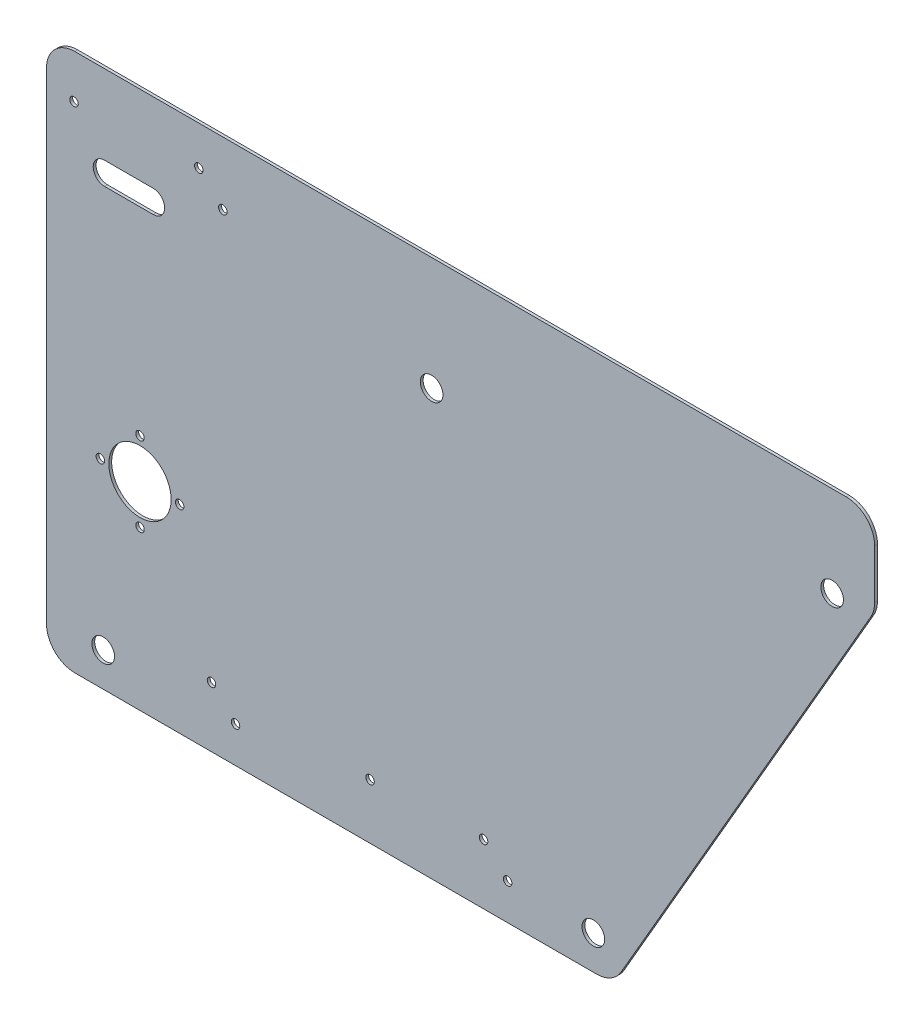
SolidWorks part; units mm, degrees
ref_plane "Front Plane" through (0, 0, 0) normal (0, 0, 1) x (1, 0, 0)
ref_plane "Top Plane" through (0, 0, 0) normal (0, 1, 0) x (1, 0, 0)
ref_plane "Right Plane" through (0, 0, 0) normal (1, 0, 0) x (0, 0, -1)
sketch "Sketch1" plane through (0, 0, 0) normal (0, 0, 1) x (1, 0, 0)
  line L0 (100, 80) -> (192.376, 80)
  line L1 (-100, -80) -> (100, -80)
  line L2 (-100, -80) -> (-100, 80)
  line L3 (-100, 80) -> (100, 80)
  line L4 (100, -80) -> (100, 80)
  line L5 (-100, -80) -> (100, 80) construction
  line L6 (-100, 80) -> (100, -80) construction
  line L7 (192.376, 80) -> (100, -80)
  line L8 (100, 80) -> (100, -80)
  line L10 (-100, 80) -> (192.376, 80)
  line L11 (-100, 80) -> (-100, 110)
  line L12 (-100, 110) -> (192.376, 110)
  line L13 (192.376, 80) -> (192.376, 110)
  point P0 (0, 0)
  dimension "D1" = 160
  dimension "D2" = 200
  dimension "D3" = 30
  dimension "D4" = 30
extrude "Boss-Extrude1" add sketch "Sketch1" along normal blind 1 contours L1 L4 L3 L2 | L7 L0 L4 | L11 L10 L13 L12
fillet "Fillet1" radius 10 5 edges at (100, -80, 0.5) (-100, -80, 0.5) (192.376, 110, 0.5) (-100, 110, 0.5) (192.376, 80, 0.5)
sketch "Sketch2" plane through (0, 0, 1) normal (0, 0, 1) x (1, 0, 0)
  line L0 (-90, -80) -> (94.2265, -80) construction
  line L1 (191.0363, 77.6795) -> (102.8868, -75) construction
  line L2 (-100, -70) -> (-100, 100) construction
  line L3 (-90, 110) -> (182.376, 110) construction
  line L4 (-79.5166, 78) -> (-62.3003, 78) construction
  line L7 (-100, -70) -> (-100, 100) construction
  line L9 (-79.5166, 82) -> (-62.3003, 82)
  line L10 (-79.5166, 74) -> (-62.3003, 74)
  circle A0 centre (93.0718, -68) radius 4
  circle A1 centre (177.3649, 78) radius 4
  circle A2 centre (-67, -10) radius 11
  circle A3 centre (-80, -68) radius 4
  circle A4 centre (-53, -10) radius 1.5
  circle A5 centre (-67, 4) radius 1.5
  circle A6 centre (-81, -10) radius 1.5
  circle A7 centre (-67, -24) radius 1.5
  circle A10 centre (35.9573, 70) radius 4
  arc A11 (-79.5166, 82) -> (-79.5166, 74) centre (-79.5166, 78) ccw
  arc A12 (-62.3003, 74) -> (-62.3003, 82) centre (-62.3003, 78) ccw
  circle A32 centre (62.7961, -67.2426) radius 1.5
  circle A33 centre (54.3108, -58.7574) radius 1.5
  circle A34 centre (-33.2742, -67.2426) radius 1.5
  circle A35 centre (-41.7595, -58.7574) radius 1.5
  circle A36 centre (14.2259, -60.5) radius 1.5
  circle A37 centre (-37.7547, 87.7574) radius 1.5
  circle A38 centre (-46.24, 96.2426) radius 1.5
  circle A39 centre (-90.2956, 94.5) radius 1.5
  point P12 (-70.9085, 78)
  dimension "D3" = 8
  dimension "D4" = 8
  dimension "D9" = 22
  dimension "D10" = 8
  dimension "D12" = 3
  dimension "D13" = 3
  dimension "D14" = 3
  dimension "D15" = 3
  dimension "D16" = 14
  dimension "D20" = 4
  dimension "D22" = 8
  dimension "D23" = 3
  dimension "D24" = 20
  dimension "D1" = 12
  dimension "D2" = 12
  dimension "D5" = 32
  dimension "D6" = 12
  dimension "D7" = 33
  dimension "D8" = 70
  dimension "D11" = 12
  dimension "D17" = 14
  dimension "D18" = 14
  dimension "D19" = 14
  dimension "D21" = 40
extrude "Cut-Extrude1" cut sketch "Sketch2" against normal blind 3
